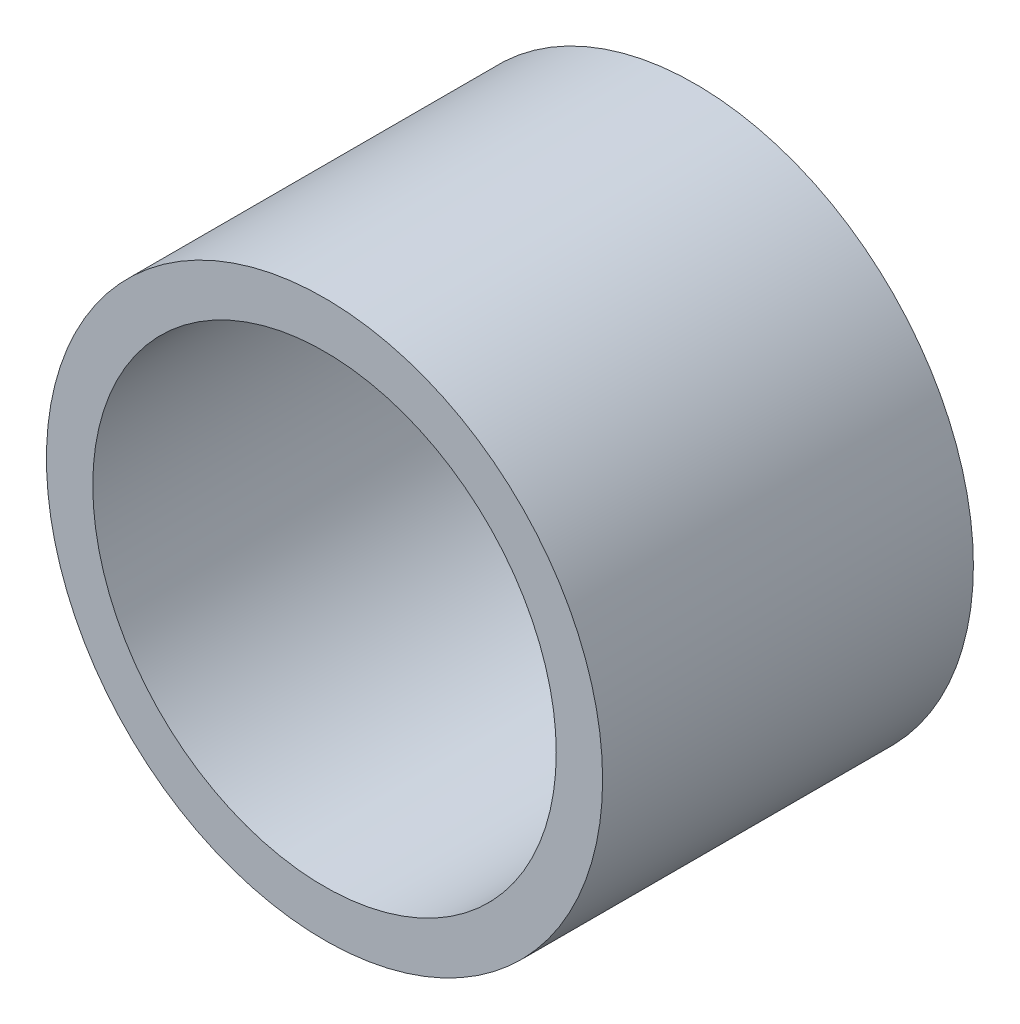
SolidWorks part; units mm, degrees
material "1060 Alloy"
ref_plane "Front Plane" through (0, 0, 0) normal (0, 0, 1) x (1, 0, 0)
ref_plane "Top Plane" through (0, 0, 0) normal (0, 1, 0) x (1, 0, 0)
ref_plane "Right Plane" through (0, 0, 0) normal (1, 0, 0) x (0, 0, -1)
sketch "Sketch1" plane through (0, 0, 0) normal (0, 0, 1) x (1, 0, 0)
  circle A0 centre (0, 0) radius 38.1
  circle A1 centre (0, 0) radius 31.75
  dimension "D1" = 76.2
  dimension "D2" = 63.5
extrude "Boss-Extrude1" add sketch "Sketch1" along normal blind 50.8
sketch "Sketch2" plane through (0, 0, 50.8) normal (0, 0, 1) x (1, 0, 0)
  circle A0 centre (0, 0) radius 38.1
